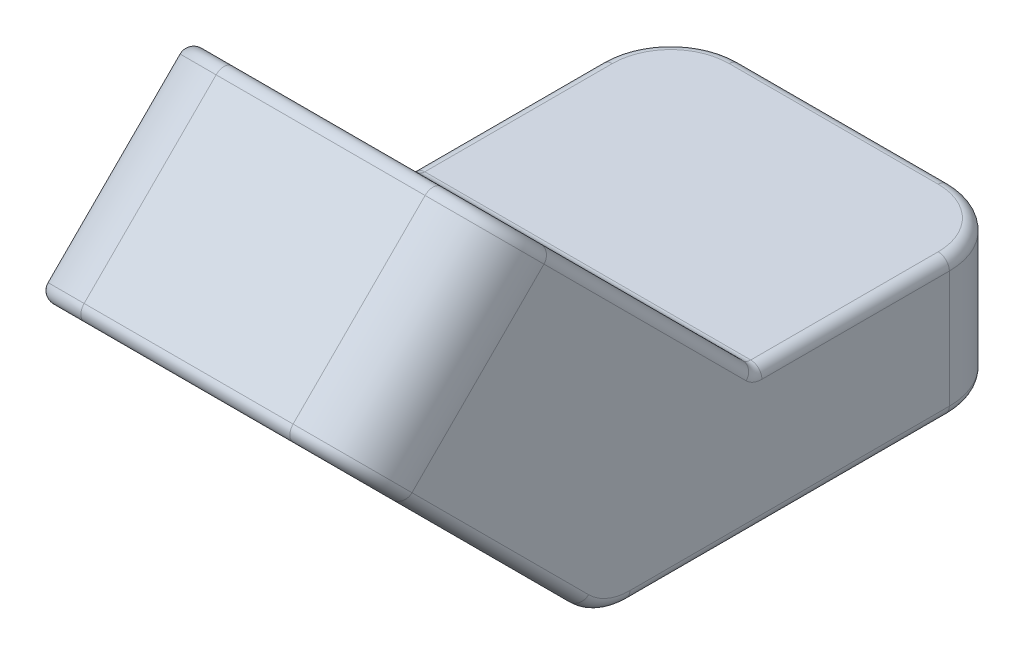
SolidWorks part; units mm, degrees
ref_plane "Front Plane" through (0, 0, 0) normal (0, 0, 1) x (1, 0, 0)
ref_plane "Top Plane" through (0, 0, 0) normal (0, 1, 0) x (1, 0, 0)
ref_plane "Right Plane" through (0, 0, 0) normal (1, 0, 0) x (0, 0, -1)
sketch "Sketch1" plane through (0, 0, 0) normal (1, 0, 0) x (0, 0, -1)
  line L0 (0, 0) -> (-19.05, 0)
  line L1 (-19.05, 0) -> (-30.2753, 11.2253)
  line L2 (-30.2753, 11.2253) -> (-23.5401, 17.9605)
  line L3 (-23.5401, 17.9605) -> (-11.9296, 6.35)
  line L4 (-11.9296, 6.35) -> (0, 6.35)
  line L5 (0, 6.35) -> (0, 0)
  point P3 (0, -0.2227)
  point P8 (-53.6484, 30.0644)
  dimension "D1" = 6.35
  dimension "D2" = 19.05
  dimension "D3" = 9.525
  dimension "D4" = 15.875
  dimension "D5" = 135
extrude "Boss-Extrude1" add sketch "Sketch1" along normal blind 15.875
sketch "Sketch2" plane through (0, -2.7898, 2.7898) normal (0, 0.7071, -0.7071) x (1, 0, 0)
  line L0 (7.9375, 0) -> (7.9375, -29.3454) construction
  line L1 (15.875, 0) -> (0, 0) construction
  line L2 (15.875, -29.3454) -> (0, -29.3454) construction
  line L3 (15.875, -12.9256) -> (0, -12.9256) construction
  circle A0 centre (7.9375, -20.2916) radius 3.302
  point P2 (12.7, -33.4127)
  point P9 (12.7, -39.8167)
  point P10 (12.7, -26.4022)
  point P11 (12.7, -23.3199)
  point P12 (12.7, -20.9017)
  dimension "D1" = 6.604
  dimension "D2" = 7.366
extrude "Cut-Extrude1" cut sketch "Sketch2" against normal through all
chamfer "Chamfer1" distance 3.175 angle 49 1 edges at (7.9375, 13.8934, 19.473)
fillet "Fillet1" radius 3.175 5 edges at (0, 3.175, 0) (15.875, 3.175, 0) (0, 14.5929, 26.9077) (15.875, 14.5929, 26.9077) (7.9375, 0, 19.05)
fillet "Fillet2" radius 0.508 23 edges at (15.875, 0.2417, 18.9499) (15.875, 4.9551, 24.0051) (14.9451, 10.5678, 29.6178) (7.9375, 11.2253, 30.2753) (0.9299, 10.5678, 29.6178) (0, 4.9551, 24.0051) (0, 0.2417, 18.9499) (0, 0, 10.4549) (0.9299, 0, 0.9299) (7.9375, 0, 0) (14.9451, 0, 0.9299) (0, 6.35, 7.5523) (0.9299, 6.35, 0.9299) (7.9375, 6.35, 0) (14.9451, 6.35, 0.9299) (0, 11.0327, 16.6123) (0.9299, 17.3029, 22.8826) (7.9375, 17.9605, 23.5401) (14.9451, 17.3029, 22.8826) (7.9375, 6.35, 11.9296) (15.875, 0, 10.4549) (15.875, 6.35, 7.5523) (15.875, 11.0327, 16.6123)
